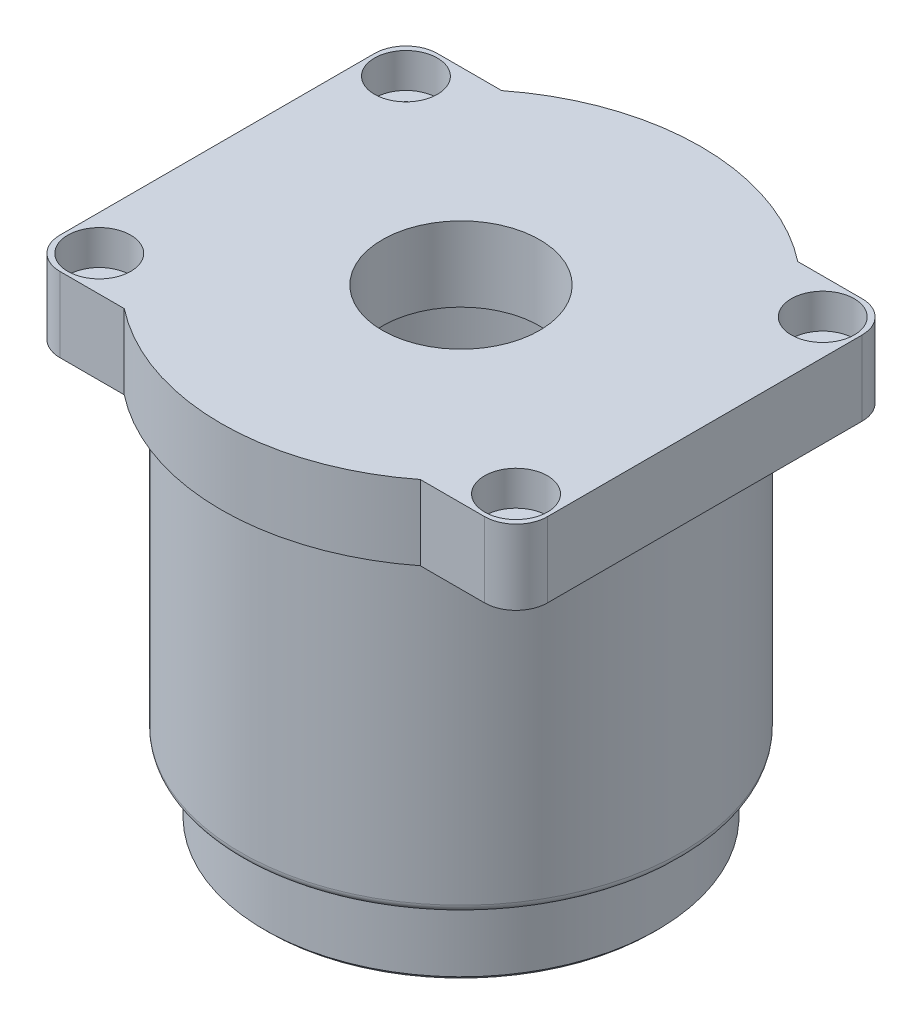
SolidWorks part; units mm, degrees
material "Ocel leštěná"
ref_plane "Přední rovina" through (0, 0, 0) normal (0, 0, 1) x (1, 0, 0)
ref_plane "Horní rovina" through (0, 0, 0) normal (0, 1, 0) x (1, 0, 0)
ref_plane "Pravá rovina" through (0, 0, 0) normal (1, 0, 0) x (0, 0, -1)
sketch "Skica1" plane through (0, 0, 0) normal (0, 1, 0) x (1, 0, 0)
  line L0 (-27, 24) -> (-18.8215, 24)
  line L1 (18.8215, 24) -> (27, 24)
  line L2 (31, 20) -> (31, -20)
  line L3 (-31, 20) -> (-31, -20)
  line L4 (-27, -24) -> (-18.8215, -24)
  line L5 (18.8215, -24) -> (27, -24)
  line L7 (-26.5, 19.5) -> (26.5, 19.5) construction
  line L8 (26.5, 19.5) -> (26.5, -19.5) construction
  line L9 (26.5, -19.5) -> (-26.5, -19.5) construction
  line L10 (-26.5, -19.5) -> (-26.5, 19.5) construction
  circle A0 centre (0, 0) radius 10
  arc A6 (-31, 20) -> (-27, 24) centre (-27, 20) cw
  arc A7 (27, 24) -> (31, 20) centre (27, 20) cw
  arc A8 (-27, -24) -> (-31, -20) centre (-27, -20) cw
  arc A9 (27, -24) -> (31, -20) centre (27, -20) ccw
  arc A10 (18.8215, 24) -> (-18.8215, 24) centre (0, 0) ccw
  arc A11 (-18.8215, -24) -> (18.8215, -24) centre (0, 0) ccw
  dimension "D1" = 39
  dimension "D2" = 53
extrude "Přidat vysunutím1" add sketch "Skica1" against normal blind 9.5
hole_wizard "Válcové zahloubení pro M4 šrouby s vnitřním šestihranem1" positions "Skica3" profile "Skica2" counterbore size "M4" standard "DIN" end condition through all
sketch "Skica3" plane through (0, 0, 0) normal (0, 1, 0) x (1, 0, 0)
  point P0 (26.5, -19.5)
sketch "Skica2" plane through (26.5, 0, 19.5) normal (1, 0, 0) x (0, 0, 1)
  line L0 (0, 0) -> (0, 9.5)
  line L1 (0, 9.5) -> (2.25, 9.5)
  line L3 (2.25, 9.5) -> (2.25, 4.4)
  line L4 (2.25, 4.4) -> (4, 4.4)
  line L5 (4, 4.4) -> (4, 0)
  line L7 (4, 0) -> (0, 0)
  line L11 (0, -6.35) -> (0, 107.95) construction
  dimension "Průměr díry skrz" = 4.5
  dimension "Hloubka díry skrz" = 9.5
  dimension "Průměr válcového zahloubení" = 8
  dimension "Hloubka válcového zahloubení" = 4.4
pattern_linear "LinPole1" count 2 spacing 53 along (-1, 0, 0) count 2 spacing 39 along (0, 0, -1) of "Válcové zahloubení pro M4 šrouby s vnitřním šestihranem1"
sketch "Skica4" plane through (0, -9.5, 0) normal (0, -1, 0) x (1, 0, 0)
  circle A0 centre (0, 0) radius 28
  circle A1 centre (0, 0) radius 20
extrude "Přidat vysunutím2" add sketch "Skica4" along normal blind 40
fillet "Zaoblit1" radius 0.5 1 edges at (0, -9.5, -28)
sketch "Skica5" plane through (0, -49.5, 0) normal (0, -1, 0) x (1, 0, 0)
  circle A0 centre (0, 0) radius 25
  circle A1 centre (0, 0) radius 12.5
extrude "Přidat vysunutím3" add sketch "Skica5" along normal blind 9.5 separate body
fillet "Zaoblit2" radius 1 1 edges at (0, -49.5, -28)
chamfer "Zkosení1" distance 0.5 angle 45 2 edges at (0, -59, -25) (0, -49.5, -25)
hole_wizard "M4 závit1" positions "3DSkica1" profile "Skica6" tap size "M4" standard "ISO"
sketch3d "3DSkica1"
  point P0 (14.8993, -54.25, -20.0752)
  dimension "D1" = 4.75
sketch "Skica6" plane through (14.8993, -54.25, -20.0752) normal (0, 1, 0) x (-0.803, 0, -0.596)
  line L0 (0, 0) -> (0, 12.4914)
  line L1 (0, 12.4914) -> (1.65, 11.5)
  line L2 (1.65, 11.5) -> (1.65, 0.375)
  line L3 (1.65, 0.375) -> (2.025, 0)
  line L5 (2.025, 0) -> (0, 0)
  line L6 (-1.65, 0.375) -> (-2.025, 0) construction
  line L10 (0, 12.4914) -> (-1.65, 11.5) construction
  line L11 (0, -6.35) -> (0, 107.95) construction
  dimension "Průměr závitníku" = 3.3
  dimension "Hloubka závitníku" = 11.5
  dimension "Průměr blíz. kuž. zahloubení" = 4.05
  dimension "Úhel blíz. kuž. zahloubení" = 90
  dimension "Úhel vrtání" = 118
cosmetic thread "Závit díry1" parameters "D1"=8, "D2"=4
sketch "Skica7" plane through (0, -59, 0) normal (0, -1, 0) x (1, 0, 0)
  circle A0 centre (0, 0) radius 20
extrude "Odebrat vysunutím1" cut sketch "Skica7" against normal blind 0.5
fillet "Zaoblit3" radius 0.25 1 edges at (0, -59, -20)
